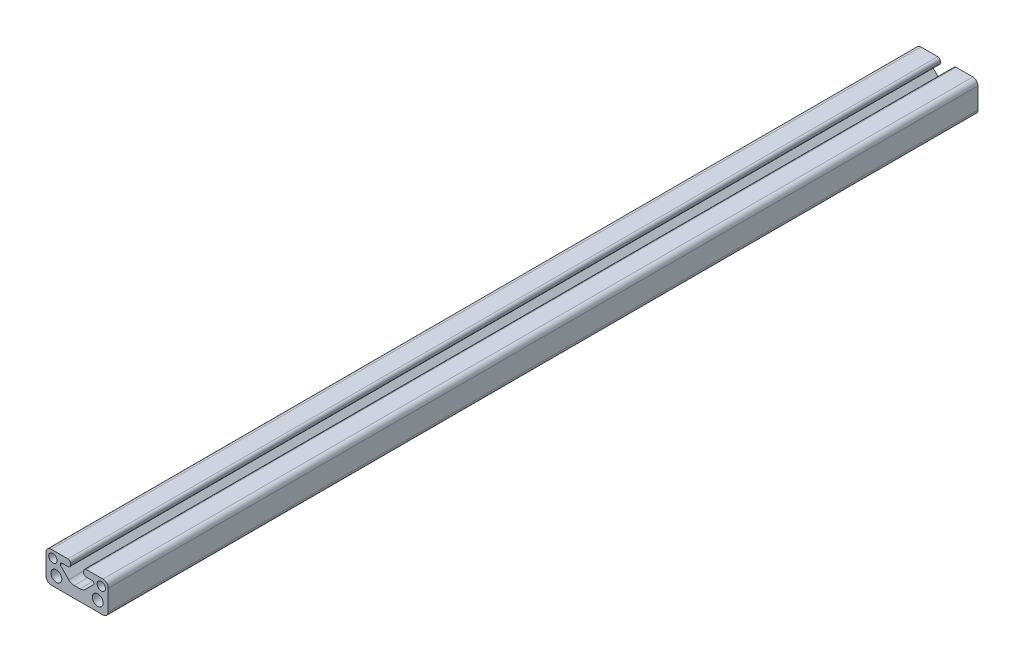
SolidWorks part; units mm, degrees
ref_plane "Front Plane" through (0, 0, 0) normal (0, 0, 1) x (1, 0, 0)
ref_plane "Top Plane" through (0, 0, 0) normal (0, 1, 0) x (1, 0, 0)
ref_plane "Right Plane" through (0, 0, 0) normal (1, 0, 0) x (0, 0, -1)
ref_plane "Plane1" through (0, 0, -533.4) normal (0, 0, -1) x (-1, 0, 0)
sketch "Sketch1" plane through (0, 0, -533.4) normal (0, 0, -1) x (-1, 0, 0)
  line L0 (19.05, 3.175) -> (19.05, 15.875)
  line L1 (15.875, 19.05) -> (5.6388, 19.05)
  line L2 (4.064, 17.4752) -> (4.064, 16.5608)
  line L3 (5.6388, 14.986) -> (9.398, 14.986)
  line L4 (10.287, 14.097) -> (10.287, 13.7794)
  line L5 (10.0266, 13.1508) -> (5.125, 8.2492)
  line L6 (1.7664, 6.858) -> (-1.7664, 6.858)
  line L7 (-5.125, 8.2492) -> (-10.0266, 13.1508)
  line L8 (-10.287, 13.7794) -> (-10.287, 14.097)
  line L9 (-9.398, 14.986) -> (-5.6388, 14.986)
  line L10 (-4.064, 16.5608) -> (-4.064, 17.4752)
  line L11 (-5.6388, 19.05) -> (-15.875, 19.05)
  line L12 (-19.05, 15.875) -> (-19.05, 3.175)
  line L13 (-15.875, 0) -> (15.875, 0)
  circle A0 centre (14.8488, 14.8014) radius 2.5527
  circle A1 centre (12.7, 6.35) radius 3.3274
  circle A2 centre (-12.7, 6.35) radius 3.3274
  circle A3 centre (-14.8488, 14.8014) radius 2.5527
  arc A4 (19.05, 15.875) -> (15.875, 19.05) centre (15.875, 15.875) ccw
  arc A5 (5.6388, 19.05) -> (4.064, 17.4752) centre (5.6388, 17.4752) ccw
  arc A6 (4.064, 16.5608) -> (5.6388, 14.986) centre (5.6388, 16.5608) ccw
  arc A7 (9.398, 14.986) -> (10.287, 14.097) centre (9.398, 14.097) cw
  arc A8 (10.287, 13.7794) -> (10.0266, 13.1508) centre (9.398, 13.7794) cw
  arc A9 (5.125, 8.2492) -> (1.7664, 6.858) centre (1.7664, 11.6078) cw
  arc A10 (-1.7664, 6.858) -> (-5.125, 8.2492) centre (-1.7664, 11.6078) cw
  arc A11 (-10.0266, 13.1508) -> (-10.287, 13.7794) centre (-9.398, 13.7794) cw
  arc A12 (-10.287, 14.097) -> (-9.398, 14.986) centre (-9.398, 14.097) cw
  arc A13 (-5.6388, 14.986) -> (-4.064, 16.5608) centre (-5.6388, 16.5608) ccw
  arc A14 (-4.064, 17.4752) -> (-5.6388, 19.05) centre (-5.6388, 17.4752) ccw
  arc A15 (-15.875, 19.05) -> (-19.05, 15.875) centre (-15.875, 15.875) ccw
  arc A16 (-19.05, 3.175) -> (-15.875, 0) centre (-15.875, 3.175) ccw
  arc A17 (15.875, 0) -> (19.05, 3.175) centre (15.875, 3.175) ccw
extrude "Boss-Extrude1" add sketch "Sketch1" against normal blind 533.4
